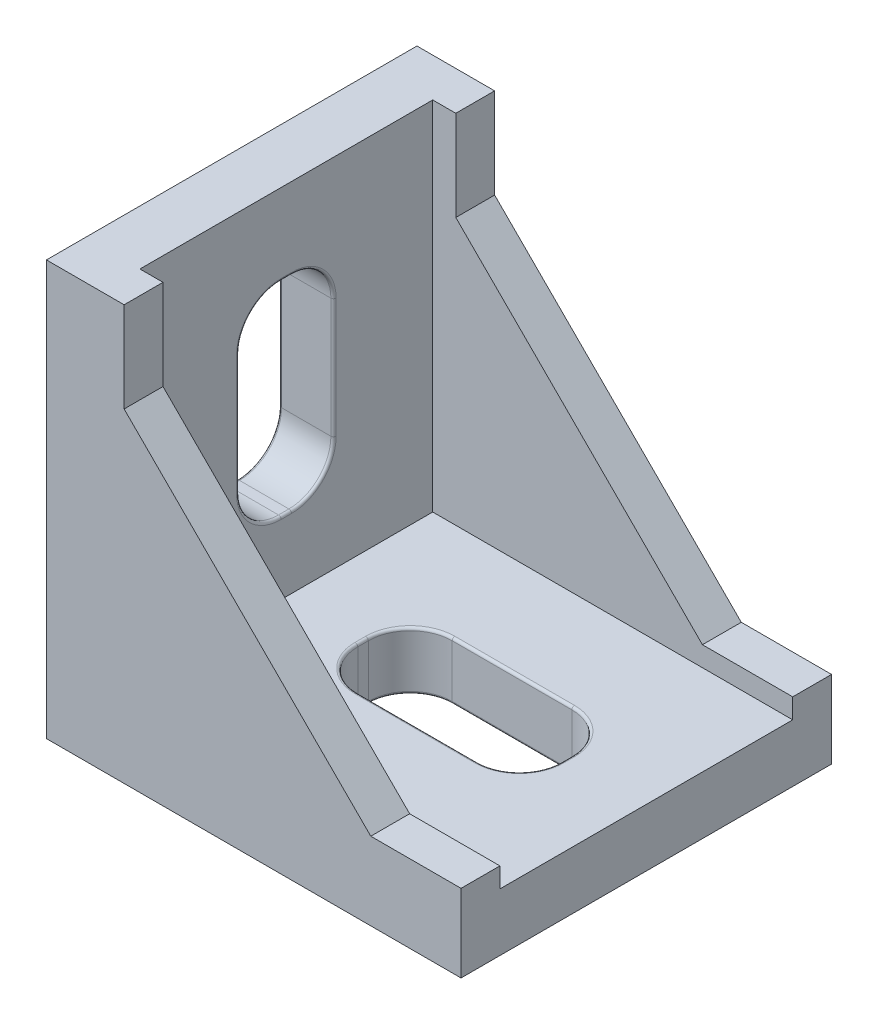
SolidWorks part; units mm, degrees
material "1.4000 (X6Cr13)"
ref_plane "Plan de face" through (0, 0, 0) normal (0, 0, 1) x (1, 0, 0)
ref_plane "Plan de dessus" through (0, 0, 0) normal (0, 1, 0) x (1, 0, 0)
ref_plane "Plan de droite" through (0, 0, 0) normal (1, 0, 0) x (0, 0, -1)
sketch "Esquisse1" plane through (0, 0, 0) normal (0, 0, 1) x (1, 0, 0)
  line L0 (0, 0) -> (39.5, 0)
  line L1 (0, 0) -> (0, 39.5)
  line L2 (39.5, 0) -> (39.5, 7.4)
  line L3 (39.5, 7.4) -> (30.9, 7.4)
  line L4 (0, 39.5) -> (7.4, 39.5)
  line L5 (7.4, 39.5) -> (7.4, 30.9)
  line L6 (7.4, 30.9) -> (30.9, 7.4)
  dimension "D1" = 39.5
  dimension "D2" = 39.5
  dimension "D3" = 7.4
  dimension "D4" = 8.6
  dimension "D5" = 7.4
  dimension "D6" = 8.6
extrude "Boss.-Extru.1" add sketch "Esquisse1" against normal blind 35.3
sketch "Esquisse2" plane through (0, 39.5, 0) normal (0, 1, 0) x (1, 0, 0)
  line L0 (7.4, 0) -> (7.4, 3.704) construction
  line L1 (7.4, 35.3) -> (7.4, 0) construction
  line L2 (7.4, 35.3) -> (7.4, 31.6) construction
  line L3 (7.4, 35.3) -> (7.4, 0) construction
  line L4 (0, 0) -> (5.2023, 0) construction
  line L5 (7.4, 0) -> (0, 0) construction
  line L6 (5.2023, 0) -> (5.2023, 35.3) construction
  line L7 (7.4, 35.3) -> (0, 35.3) construction
  line L8 (7.4, 3.704) -> (5.2023, 3.704) construction
  line L9 (5.2023, 3.704) -> (5.2023, 31.6) construction
  line L10 (5.2023, 31.6) -> (7.4, 31.6) construction
  line L11 (39.5, 35.3) -> (39.5, 0) construction
  line L12 (5.2023, 3.704) -> (39.5, 3.704)
  line L13 (5.2023, 3.704) -> (5.2023, 31.6)
  line L14 (5.2023, 31.6) -> (39.5, 31.6)
  line L15 (39.5, 3.704) -> (39.5, 31.6)
  dimension "D1" = 3.704
  dimension "D2" = 3.7
extrude "Enlèv. mat.-Extru.1" cut sketch "Esquisse2" against normal blind 34
sketch "Esquisse3" plane through (5.2023, 0, 0) normal (1, 0, 0) x (0, 0, -1)
  line L0 (3.704, 5.5) -> (31.6, 5.5) construction
  line L1 (17.652, 5.5) -> (17.652, 39.5) construction
  line L2 (31.6, 39.5) -> (3.704, 39.5) construction
  line L3 (17.652, 39.5) -> (17.652, 31.7483) construction
  line L4 (17.652, 31.7483) -> (13.157, 31.7483) construction
  line L5 (13.157, 31.7483) -> (13.157, 12.3547) construction
  line L6 (13.157, 12.3547) -> (17.652, 12.3547) construction
  line L7 (18.147, 12.3547) -> (17.157, 12.3547)
  line L8 (13.157, 16.3547) -> (13.157, 27.7483)
  line L9 (17.157, 31.7483) -> (18.147, 31.7483)
  line L10 (22.147, 16.3547) -> (22.147, 27.7483)
  arc A0 (22.147, 16.3547) -> (18.147, 12.3547) centre (18.147, 16.3547) cw
  arc A1 (17.157, 12.3547) -> (13.157, 16.3547) centre (17.157, 16.3547) cw
  arc A2 (22.147, 27.7483) -> (18.147, 31.7483) centre (18.147, 27.7483) ccw
  arc A3 (13.157, 27.7483) -> (17.157, 31.7483) centre (17.157, 27.7483) cw
  point P16 (22.147, 12.3547)
  point P22 (22.147, 31.7483)
  dimension "D2" = 4
  dimension "D1" = 4.495
extrude "Enlèv. mat.-Extru.5" cut sketch "Esquisse3" against normal blind 34
fillet "Congé1" radius 0.25 16 edges at (0, 22.0515, -22.147) (0, 30.5767, -20.9755) (0, 31.7483, -17.652) (0, 30.5767, -14.3286) (0, 22.0515, -13.157) (0, 13.5262, -14.3286) (0, 12.3547, -17.652) (5.2023, 22.0515, -13.157) (5.2023, 30.5767, -14.3286) (5.2023, 31.7483, -17.652) (5.2023, 30.5767, -20.9755) (5.2023, 22.0515, -22.147) (5.2023, 13.5262, -20.9755) (5.2023, 12.3547, -17.652) (0, 13.5262, -20.9755) (5.2023, 13.5262, -14.3286)
sketch "Esquisse4" plane through (0, 5.5, 0) normal (0, 1, 0) x (1, 0, 0)
  line L0 (39.5, 3.704) -> (39.5, 31.6) construction
  line L1 (39.5, 17.652) -> (5.2023, 17.652) construction
  line L2 (5.2023, 31.6) -> (5.2023, 3.704) construction
  line L3 (39.5, 17.652) -> (31.9012, 17.652) construction
  line L4 (31.9012, 17.652) -> (31.9012, 22.1528) construction
  line L5 (31.9012, 22.1528) -> (12.5083, 22.1528) construction
  line L6 (12.5083, 22.1528) -> (12.5083, 17.652) construction
  line L7 (12.5083, 17.1512) -> (12.5083, 18.1528)
  line L8 (16.5083, 22.1528) -> (27.9012, 22.1528)
  line L9 (31.9012, 18.1528) -> (31.9012, 17.1512)
  line L10 (16.5083, 13.1512) -> (27.9012, 13.1512)
  arc A0 (27.9012, 22.1528) -> (31.9012, 18.1528) centre (27.9012, 18.1528) cw
  arc A1 (27.9012, 13.1512) -> (31.9012, 17.1512) centre (27.9012, 17.1512) ccw
  arc A2 (16.5083, 13.1512) -> (12.5083, 17.1512) centre (16.5083, 17.1512) cw
  arc A3 (12.5083, 18.1528) -> (16.5083, 22.1528) centre (16.5083, 18.1528) cw
  point P19 (31.9012, 13.1512)
  point P22 (12.5083, 13.1512)
  dimension "D1" = 4
extrude "Enlèv. mat.-Extru.6" cut sketch "Esquisse4" against normal blind 34
fillet "Congé2" radius 0.25 16 edges at (22.2047, 0, -13.1512) (30.7296, 0, -14.3228) (31.9012, 0, -17.652) (30.7296, 0, -20.9812) (22.2047, 0, -22.1528) (13.6799, 0, -20.9812) (12.5083, 0, -17.652) (12.5083, 5.5, -17.652) (13.6799, 5.5, -20.9812) (22.2047, 5.5, -22.1528) (30.7296, 5.5, -20.9812) (31.9012, 5.5, -17.652) (30.7296, 5.5, -14.3228) (22.2047, 5.5, -13.1512) (13.6799, 0, -14.3228) (13.6799, 5.5, -14.3228)
sketch "Esquisse5" plane through (0, 0, 0) normal (0, -1, 0) x (1, 0, 0)
  line L0 (32.1512, -17.652) -> (0, -17.65) construction
  line L1 (32.1512, -17.1512) -> (32.1512, -18.1528) construction
  line L2 (0, -35.3) -> (0, 0) construction
  line L3 (0, -17.65) -> (3.598, -17.6502) construction
  line L4 (3.598, -17.6502) -> (3.598, -21.5752) construction
  line L5 (3.598, -21.5752) -> (7.598, -21.5752) construction
  line L6 (3.598, -17.6502) -> (3.598, -21.5752)
  line L7 (3.598, -21.5752) -> (7.598, -21.5752)
  line L8 (7.598, -21.5752) -> (7.598, -17.6505)
  line L9 (7.5985, -13.7257) -> (7.598, -17.6505)
  line L10 (3.5985, -13.7252) -> (7.5985, -13.7257)
  line L11 (3.598, -17.6502) -> (3.5985, -13.7252)
  line L12 (22.2047, -22.4028) -> (22.2047, 2.5888) construction
  line L13 (27.9012, -22.4028) -> (16.5083, -22.4028) construction
  dimension "D1" = 3.925
  dimension "D2" = 4
extrude "Boss.-Extru.2" add sketch "Esquisse5" along normal blind 2
chamfer "Chanfrein1" distance 1.5 angle 45 4 edges at (7.5982, -2, -15.6881) (7.598, -2, -19.6128) (3.598, -2, -19.6127) (3.5982, -2, -15.6877)
sketch "Esquisse6" plane through (0, 0, 0) normal (0, -1, 0) x (1, 0, 0)
  line L0 (6.098, -17.6503) -> (39.5, -17.65) construction
  line L1 (39.5, -35.3) -> (39.5, 0) construction
  line L2 (39.5, -17.65) -> (35.8956, -17.65) construction
  line L3 (7.598, -21.5752) -> (39.5, -21.5752) construction
  line L4 (35.8956, -17.65) -> (35.8956, -21.5752) construction
  line L5 (32.1512, -17.652) -> (32.1512, -21.5752) construction
  line L6 (32.1512, -17.1512) -> (32.1512, -18.1528) construction
  line L7 (32.1512, -21.5752) -> (35.8956, -21.5752) construction
  line L9 (35.8956, -21.5752) -> (32.2728, -21.5752)
  line L10 (35.8956, -21.5752) -> (35.8956, -13.6752)
  line L11 (35.8956, -13.6752) -> (32.2728, -13.6752)
  line L12 (32.2728, -21.5752) -> (32.2728, -13.6752)
  dimension "D1" = 7.9
extrude "Boss.-Extru.4" add sketch "Esquisse6" along normal blind 2
chamfer "Chanfrein2" distance 1.5 angle 45 2 edges at (32.2728, -2, -17.6252) (35.8956, -2, -17.6252)
sketch "Esquisse7" plane through (0, 0, 0) normal (-1, 0, 0) x (0, 0, 1)
  line L0 (0, 0) -> (-35.3, 0) construction
  line L1 (-17.6502, 0) -> (-17.6502, 39.5) construction
  line L2 (-35.3, 39.5) -> (0, 39.5) construction
  line L3 (-17.6502, 0) -> (-17.6502, 3.2126) construction
  line L4 (-17.6502, 3.2126) -> (-21.5752, 3.2126) construction
  line L5 (-21.5752, 3.2126) -> (-21.5752, 7.8126) construction
  line L6 (-13.7252, 3.2126) -> (-21.5752, 3.2126)
  line L7 (-21.5752, 3.2126) -> (-21.5752, 7.8126)
  line L8 (-21.5752, 7.8126) -> (-13.7252, 7.8126)
  line L9 (-13.7252, 3.2126) -> (-13.7252, 7.8126)
  line L10 (-17.6502, 39.5) -> (-17.6502, 37.402) construction
  line L11 (-17.6502, 37.402) -> (-21.5752, 37.402) construction
  line L12 (-21.5752, 37.402) -> (-21.5752, 32.7975) construction
  line L13 (-21.5752, 32.7975) -> (-17.6502, 32.7975) construction
  line L14 (-13.7252, 32.7975) -> (-21.5752, 32.7975)
  line L15 (-21.5752, 32.7975) -> (-21.5752, 37.402)
  line L16 (-21.5752, 37.402) -> (-13.7252, 37.402)
  line L17 (-13.7252, 32.7975) -> (-13.7252, 37.402)
  point P14 (-17.6502, 7.8126)
  dimension "D1" = 3.925
  dimension "D2" = 4.6
extrude "Boss.-Extru.5" add sketch "Esquisse7" along normal blind 2
chamfer "Chanfrein3" distance 1.5 angle 45 4 edges at (-2, 37.402, -17.6502) (-2, 32.7975, -17.6502) (-2, 7.8126, -17.6502) (-2, 3.2126, -17.6502)
